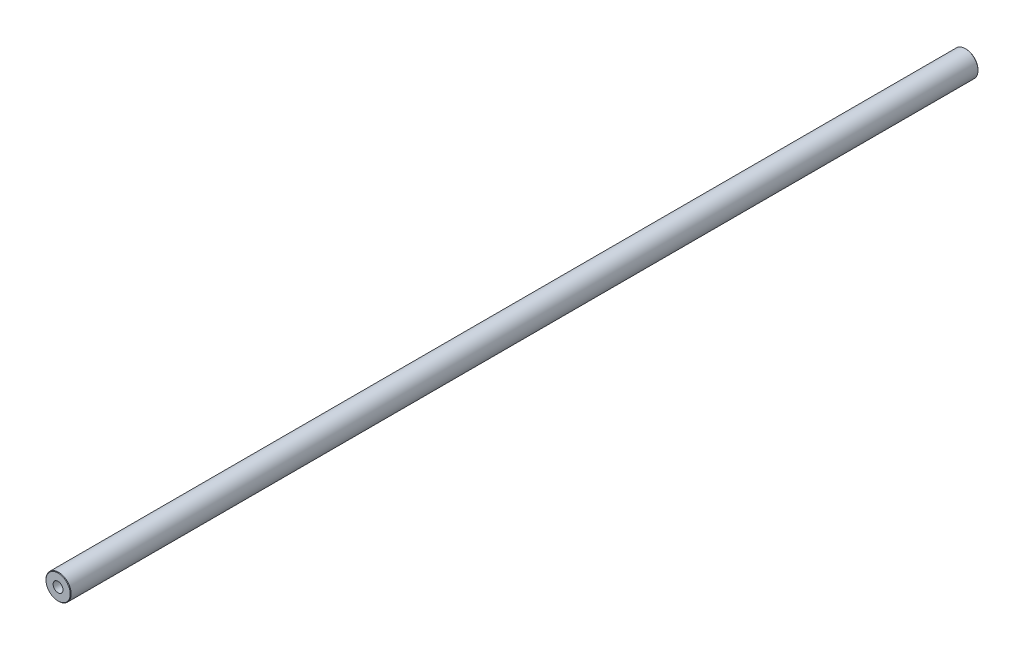
SolidWorks part; units mm, degrees
ref_plane "Front Plane" through (0, 0, 0) normal (0, 0, 1) x (1, 0, 0)
ref_plane "Top Plane" through (0, 0, 0) normal (0, 1, 0) x (1, 0, 0)
ref_plane "Right Plane" through (0, 0, 0) normal (1, 0, 0) x (0, 0, -1)
sketch "Sketch1" plane through (0, 0, 0) normal (0, 0, 1) x (1, 0, 0)
  circle A0 centre (0, 0) radius 6.35 construction
  dimension "Diameter" = 12.7
sketch "Sketch2" plane through (0, 0, 0) normal (1, 0, 0) x (0, 0, -1)
  line L0 (228.6, 0) -> (-228.6, 0) construction
  point P0 (-182.88, 0)
  point P3 (0, 0)
  point P4 (182.88, 0)
  point P6 (-160.02, 0)
  point P7 (160.02, 0)
  dimension "Length" = 457.2
  dimension "D1" = 45.72
  dimension "D2" = 45.72
  dimension "D3" = 68.58
  dimension "D4" = 68.58
sketch "Sketch3" plane through (0, 0, 0) normal (0, 0, 1) x (1, 0, 0)
  circle A0 centre (0, 0) radius 6.35 construction
  circle A1 centre (0, 0) radius 6.35
extrude "Boss-Extrude1" add sketch "Sketch3" along normal up to vertex (228.6 mm away) and the other way up to vertex (228.6 mm away) up to point (0, 0, 228.6) other way up to point (0, 0, -228.6)
chamfer "Chamfer1" distance 0.254 angle 45 2 edges at (6.35, 0, 228.6) (6.35, 0, -228.6)
hole_wizard "M6x1.0 Tapped Hole1" positions "3DSketch1" profile "Sketch6" tap size "M6x1.0" standard "ANSI Metric"
sketch3d "3DSketch1"
  line L0 (0, 0, -228.346) -> (0, 0, -228.6) construction
  circle A0 centre (0, 0, 228.6) radius 6.096 construction
  point P0 (0, 0, -228.6)
  point P4 (0, 0, 228.6)
  point P5 (0, 0, 0)
  point P8 (0, 0, 234.696)
sketch "Sketch6" plane through (0, 0, -228.6) normal (1, 0, 0) x (0, 1, 0)
  line L0 (0, 0) -> (0, 26.5022)
  line L1 (0, 26.5022) -> (2.5, 25)
  line L2 (2.5, 25) -> (2.5, 0)
  line L5 (2.5, 0) -> (0, 0)
  line L10 (0, 26.5022) -> (-2.5, 25) construction
  line L11 (0, -6.35) -> (0, 107.95) construction
  dimension "Tap Drill Dia." = 5
  dimension "Tap Drill Depth" = 25
  dimension "Drill Angle" = 118
cosmetic thread "Hole Thread1" parameters "D1"=12, "D2"=6
cosmetic thread "Hole Thread2" parameters "D1"=12, "D2"=6
equation "\"D1@Chamfer1\"=\"Diameter@Sketch1\"*.02"
equation "\"D1@Sketch2\"=\"D2@Sketch2\""
equation "\"D2@Sketch2\"=\"Length@Sketch2\"*.1"
equation "\"D3@Sketch2\"=\"Length@Sketch2\"*.15"
equation "\"D4@Sketch2\"=\"D3@Sketch2\""
